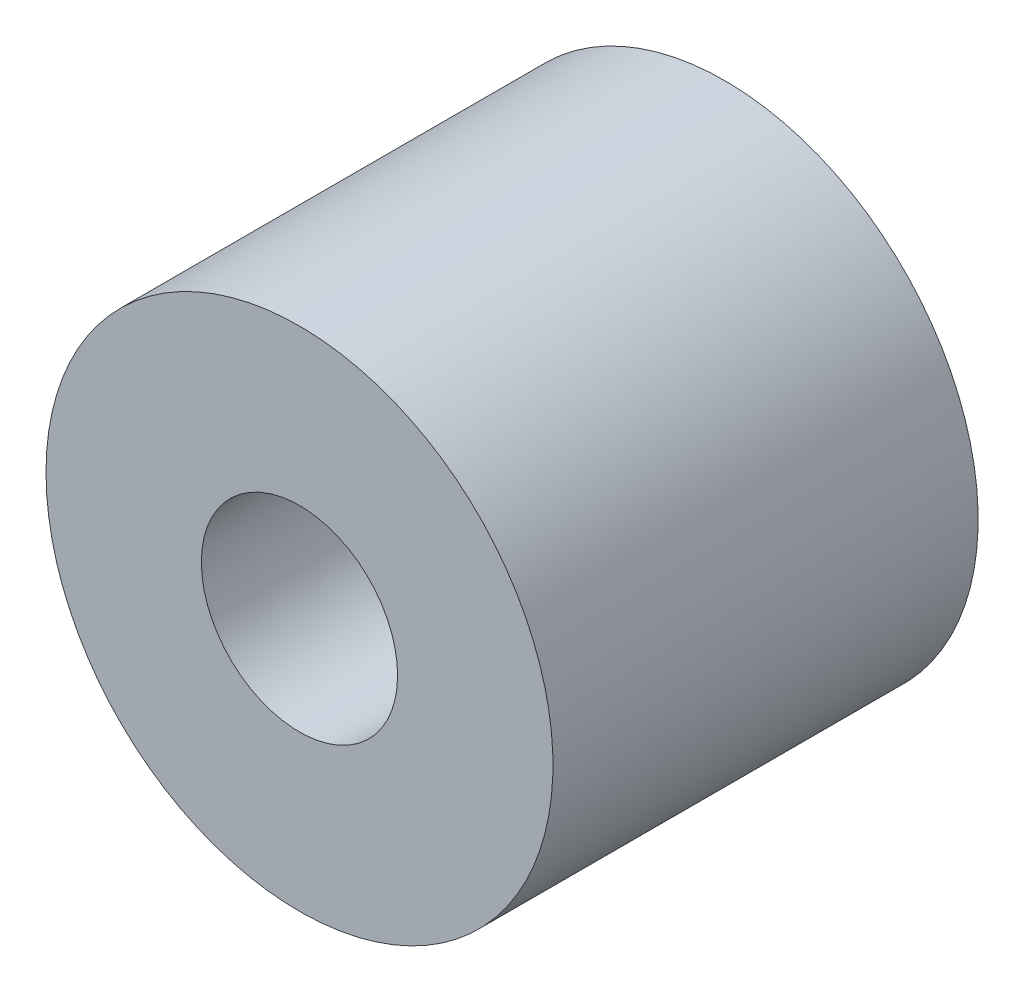
SolidWorks part; units mm, degrees
material "1060 合金"
ref_plane "前视基准面" through (0, 0, 0) normal (0, 0, 1) x (1, 0, 0)
ref_plane "上视基准面" through (0, 0, 0) normal (0, 1, 0) x (1, 0, 0)
ref_plane "右视基准面" through (0, 0, 0) normal (1, 0, 0) x (0, 0, -1)
sketch "草图1" plane through (0, 0, 0) normal (0, 0, 1) x (1, 0, 0)
  circle A0 centre (0, 0) radius 7.75
  circle A1 centre (0, 0) radius 3
  dimension "D1" = 6
  dimension "D2" = 15.5
extrude "凸台-拉伸1" add sketch "草图1" along normal blind 13
move or copy body "实体-移动/复制1" [suppressed] bodies to move or copy 106
